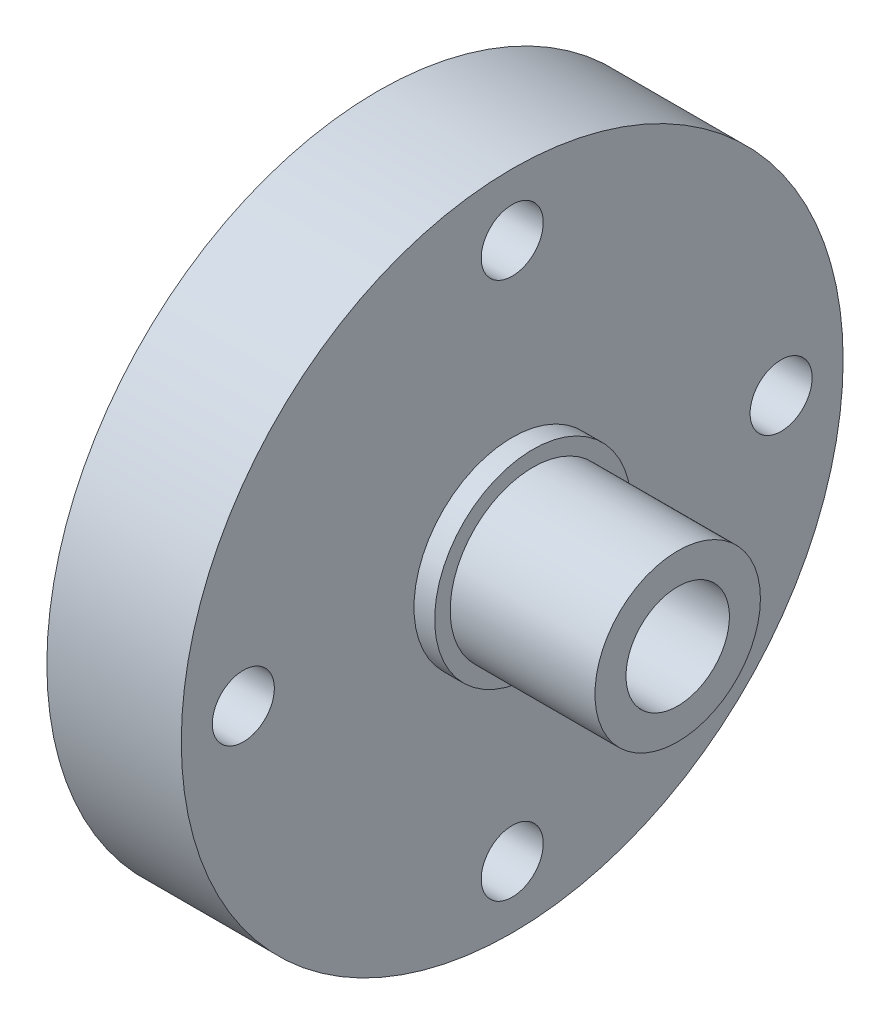
SolidWorks part; units mm, degrees
ref_plane "Front Plane" through (0, 0, 0) normal (0, 0, 1) x (1, 0, 0)
ref_plane "Top Plane" through (0, 0, 0) normal (0, 1, 0) x (1, 0, 0)
ref_plane "Right Plane" through (0, 0, 0) normal (1, 0, 0) x (0, 0, -1)
sketch "Sketch1" plane through (0, 0, 0) normal (1, 0, 0) x (0, 0, -1)
  circle A0 centre (0, 0) radius 16
  circle A1 centre (0, 0) radius 2.5
  dimension "D1" = 5
  dimension "D2" = 32
extrude "Boss-Extrude1" add sketch "Sketch1" along normal blind 6.5
sketch "Sketch2" plane through (6.5, 0, 0) normal (1, 0, 0) x (0, 0, -1)
  circle A0 centre (0, 13) radius 1.5
  circle A1 centre (0, 0) radius 2.5 construction
  circle A7 centre (13, 0) radius 1.5
  circle A8 centre (0, -13) radius 1.5
  circle A9 centre (-13, 0) radius 1.5
  point P13 (0, 0)
  point P17 (0, 0)
  dimension "D1" = 13
  dimension "D2" = 3
extrude "Cut-Extrude1" cut sketch "Sketch2" against normal through all
sketch "Sketch4" plane through (6.5, 0, 0) normal (1, 0, 0) x (0, 0, -1)
  circle A0 centre (0, 0) radius 2.5 construction
  circle A1 centre (0, 0) radius 2.5
  circle A2 centre (0, 0) radius 4.75
  dimension "D1" = 9.5
extrude "Boss-Extrude2" add sketch "Sketch4" along normal blind 1
sketch "Sketch5" plane through (7.5, 0, 0) normal (1, 0, 0) x (0, 0, -1)
  circle A0 centre (0, 0) radius 2.5 construction
  circle A1 centre (0, 0) radius 2.5
  circle A2 centre (0, 0) radius 4
  dimension "D1" = 8
extrude "Boss-Extrude3" add sketch "Sketch5" along normal blind 7
